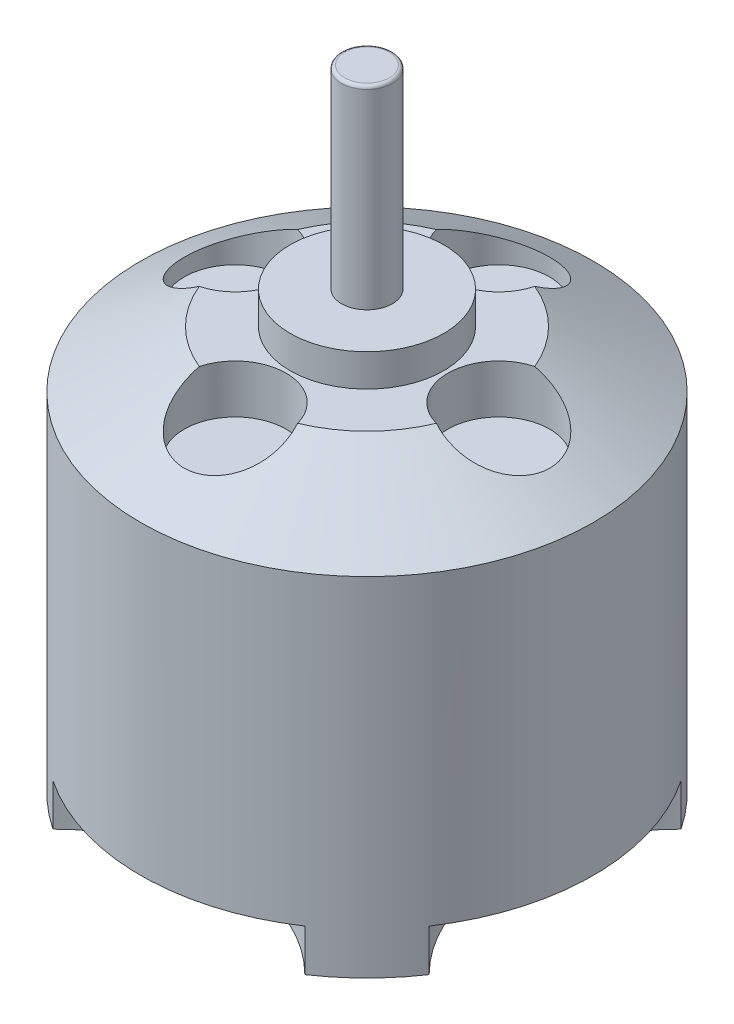
SolidWorks part; units mm, degrees
ref_plane "Front Plane" through (0, 0, 0) normal (0, 0, 1) x (1, 0, 0)
ref_plane "Top Plane" through (0, 0, 0) normal (0, 1, 0) x (1, 0, 0)
ref_plane "Right Plane" through (0, 0, 0) normal (1, 0, 0) x (0, 0, -1)
sketch "Sketch1" plane through (0, 0, 0) normal (0, 1, 0) x (1, 0, 0)
  circle A0 centre (0, 0) radius 14
  dimension "D1" = 28
extrude "Boss-Extrude1" add sketch "Sketch1" along normal blind 25
chamfer "Chamfer1" distance 3.5 angle 60 1 edges at (0, 25, 14)
sketch "Sketch2" plane through (0, 25, 0) normal (0, 1, 0) x (1, 0, 0)
  circle A0 centre (0, 0) radius 4.75
  dimension "D1" = 9.5
extrude "Boss-Extrude2" add sketch "Sketch2" along normal blind 2
sketch "Sketch3" plane through (0, 27, 0) normal (0, 1, 0) x (1, 0, 0)
  circle A0 centre (0, 0) radius 1.575
  dimension "D1" = 3.15
extrude "Boss-Extrude3" add sketch "Sketch3" along normal blind 12
sketch "Sketch4" plane through (0, 0, 0) normal (0, -1, 0) x (1, 0, 0)
  line L0 (-19.4, 0) -> (0, 0) construction
  line L1 (19.4, 0) -> (0, 0) construction
  line L2 (0, 19.4) -> (0, 0) construction
  line L3 (0, 0) -> (0, -19.4) construction
  circle A0 centre (-19.4, 0) radius 11
  circle A1 centre (0, 19.4) radius 11
  circle A2 centre (19.4, 0) radius 11
  circle A3 centre (0, -19.4) radius 11
  circle A4 centre (0, 0) radius 14 construction
  point P8 (-8.4, 0)
  point P11 (-14, 0)
  dimension "D1" = 22
  dimension "D2" = 5.6
extrude "Cut-Extrude1" cut sketch "Sketch4" against normal blind 2.6
sketch "Sketch5" plane through (0, 0, 0) normal (0, -1, 0) x (1, 0, 0)
  line L0 (0, 0) -> (-9.3628, 9.3628) construction
  line L1 (-9.3628, 9.3628) -> (8.8261, -8.8261) construction
  line L2 (0, 0) -> (-8.8261, -8.8261) construction
  line L3 (-8.8261, -8.8261) -> (9.3628, 9.3628) construction
  circle A0 centre (-6.7175, -6.7175) radius 1.5
  circle A1 centre (-5.6569, 5.6569) radius 1.5
  circle A2 centre (6.7175, 6.7175) radius 1.5
  circle A3 centre (5.6569, -5.6569) radius 1.5
  circle A4 centre (0, 0) radius 3.5
  dimension "D1" = 3
  dimension "D6" = 7
  dimension "D2" = 8
  dimension "D3" = 8
  dimension "D4" = 9.5
  dimension "D5" = 9.5
extrude "Cut-Extrude2" cut sketch "Sketch5" against normal blind 1
chamfer "Chamfer2" distance 2 angle 26 1 edges at (0, 0, -3.5)
fillet "Fillet1" radius 0.2 1 edges at (0, 39, 1.575)
sketch "Sketch6" plane through (0, 25, 0) normal (0, 1, 0) x (1, 0, 0)
  line L0 (0, 0) -> (-5, 0) construction
  line L1 (0, 0) -> (5, 0) construction
  line L2 (0, 0) -> (0, 5) construction
  line L3 (0, 0) -> (0, -5) construction
  circle A0 centre (-8.15, 0) radius 3.15
  circle A1 centre (0, 8.15) radius 3.15
  circle A2 centre (8.15, 0) radius 3.15
  circle A3 centre (0, -8.15) radius 3.15
  dimension "D1" = 6.3
  dimension "D2" = 5
extrude "Cut-Extrude3" cut sketch "Sketch6" against normal blind 3
